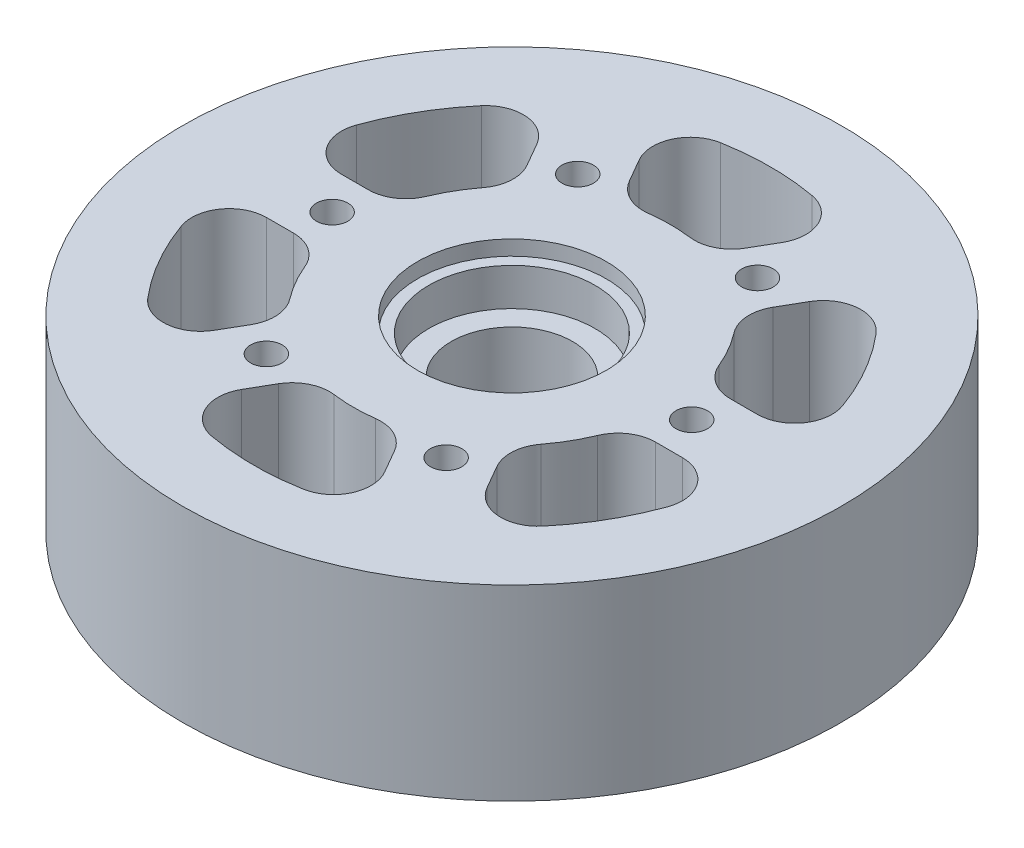
SolidWorks part; units mm, degrees
ref_plane "前视基准面" through (0, 0, 0) normal (0, 0, 1) x (1, 0, 0)
ref_plane "上视基准面" through (0, 0, 0) normal (0, 1, 0) x (1, 0, 0)
ref_plane "右视基准面" through (0, 0, 0) normal (1, 0, 0) x (0, 0, -1)
sketch "草图1" plane through (0, 0, 0) normal (0, 1, 0) x (1, 0, 0)
  circle A0 centre (0, 0) radius 52.5
  circle A1 centre (0, 0) radius 11.15
  dimension "D1" = 105
  dimension "D2" = 22.3
extrude "凸台-拉伸1" add sketch "草图1" along normal blind 25
sketch "草图2" plane through (0, 25, 0) normal (0, 1, 0) x (1, 0, 0)
  line L0 (-34.5, 0) -> (-21.15, 0)
  line L1 (-34.5, -5) -> (-21.15, -5)
  line L2 (-34.5, 5) -> (-21.15, 5)
  line L3 (-21.15, 5) -> (-20.5505, 5)
  line L4 (-21.15, -5) -> (-20.5505, -5)
  line L5 (-12.9199, 32.3779) -> (-6.2449, 20.8164)
  line L6 (-6.2449, 20.8164) -> (-5.9451, 20.2972)
  line L7 (-21.5801, 27.3779) -> (-14.9051, 15.8164)
  line L8 (-14.9051, 15.8164) -> (-14.6054, 15.2972)
  line L9 (21.5801, 27.3779) -> (14.9051, 15.8164)
  line L10 (14.9051, 15.8164) -> (14.6054, 15.2972)
  line L11 (12.9199, 32.3779) -> (6.2449, 20.8164)
  line L12 (6.2449, 20.8164) -> (5.9451, 20.2972)
  line L13 (34.5, -5) -> (21.15, -5)
  line L14 (21.15, -5) -> (20.5505, -5)
  line L15 (34.5, 5) -> (21.15, 5)
  line L16 (21.15, 5) -> (20.5505, 5)
  line L17 (12.9199, -32.3779) -> (6.2449, -20.8164)
  line L18 (6.2449, -20.8164) -> (5.9451, -20.2972)
  line L19 (21.5801, -27.3779) -> (14.9051, -15.8164)
  line L20 (14.9051, -15.8164) -> (14.6054, -15.2972)
  line L21 (-21.5801, -27.3779) -> (-14.9051, -15.8164)
  line L22 (-14.9051, -15.8164) -> (-14.6054, -15.2972)
  line L23 (-12.9199, -32.3779) -> (-6.2449, -20.8164)
  line L24 (-6.2449, -20.8164) -> (-5.9451, -20.2972)
  circle A0 centre (0, 0) radius 21.15
  circle A1 centre (0, 0) radius 34.5
  circle A2 centre (0, 0) radius 52.5 construction
  circle A3 centre (0, 0) radius 11.15 construction
  dimension "D1" = 18
  dimension "D2" = 10
  dimension "D3" = 5
  dimension "D5" = 6
  dimension "D4" = 5
extrude "切除-拉伸1" cut sketch "草图2" against normal blind 30 contours L7 A1 L2 L3 A0 L8
pattern_circular "阵列(圆周)1" count 6 over 360 about axis through (0, 25, 0) along (0, -1, 0) of "切除-拉伸1"
fillet "圆角1" radius 5 24 edges at (20.5505, 12.5, -5) (14.6054, 12.5, -15.2972) (21.398, 12.5, -27.0624) (34.1358, 12.5, -5) (-20.5505, 12.5, 5) (-14.6054, 12.5, 15.2972) (-21.398, 12.5, 27.0624) (-34.1358, 12.5, 5) (5.9451, 12.5, -20.2972) (-5.9451, 12.5, -20.2972) (-12.7378, 12.5, -32.0624) (12.7378, 12.5, -32.0624) (-14.6054, 12.5, -15.2972) (-20.5505, 12.5, -5) (-34.1358, 12.5, -5) (-5.9451, 12.5, 20.2972) (5.9451, 12.5, 20.2972) (12.7378, 12.5, 32.0624) (-12.7378, 12.5, 32.0624) (14.6054, 12.5, 15.2972) (20.5505, 12.5, 5) (34.1358, 12.5, 5) (21.398, 12.5, 27.0624) (-21.398, 12.5, -27.0624)
sketch "草图3" plane through (0, 25, 0) normal (0, 1, 0) x (1, 0, 0)
  circle A0 centre (0, 0) radius 44
  circle M2 centre (0, 0) radius 52.5
  dimension "D1" = 88
extrude "切除-拉伸2" cut sketch "草图3" against normal blind 30 contours A0 M2
sketch "草图5" plane through (0, 25, 0) normal (0, 1, 0) x (1, 0, 0)
  line L0 (0, 0) -> (24, 0)
  circle A0 centre (0, 0) radius 24
  circle A1 centre (24, 0) radius 2.1
  dimension "D1" = 48
  dimension "D2" = 4.2
extrude "切除-拉伸3" cut sketch "草图5" against normal blind 44 contours A1
pattern_circular "阵列(圆周)2" count 6 over 360 about axis through (0, 0, 0) along (0, 1, 0) of "切除-拉伸3"
sketch "草图6" plane through (0, 0, 0) normal (0, -1, 0) x (-1, 0, 0)
  arc A0 (12.5062, -0.2944) -> (12.5062, 0.2944) centre (0, 0) ccw
  arc A1 (12.237, 2.5976) -> (12.1012, 3.1706) centre (0, 0) ccw
  arc A2 (11.308, 5.3496) -> (11.0438, 5.8759) centre (0, 0) ccw
  arc A3 (9.7695, 7.8133) -> (9.391, 8.2643) centre (0, 0) ccw
  arc A4 (7.7043, 9.8557) -> (7.232, 10.2073) centre (0, 0) ccw
  arc A5 (5.2238, 11.3667) -> (4.6831, 11.6) centre (0, 0) ccw
  arc A6 (2.4616, 12.265) -> (1.8817, 12.3673) centre (0, 0) ccw
  arc A7 (-0.4332, 12.5021) -> (-1.0211, 12.4679) centre (0, 0) ccw
  arc A8 (-3.3048, 12.0652) -> (-3.8689, 11.8963) centre (0, 0) ccw
  arc A9 (-5.9981, 10.9779) -> (-6.5081, 10.6834) centre (0, 0) ccw
  arc A10 (-8.3681, 9.2987) -> (-8.7964, 8.8946) centre (0, 0) ccw
  arc A11 (-10.287, 7.1182) -> (-10.6105, 6.6263) centre (0, 0) ccw
  arc A12 (-11.6512, 4.554) -> (-11.8526, 4.0007) centre (0, 0) ccw
  arc A13 (-12.3874, 1.7443) -> (-12.4558, 1.1594) centre (0, 0) ccw
  arc A14 (-12.4558, -1.1594) -> (-12.3874, -1.7443) centre (0, 0) ccw
  arc A15 (-11.8526, -4.0007) -> (-11.6512, -4.554) centre (0, 0) ccw
  arc A16 (-10.6105, -6.6263) -> (-10.287, -7.1182) centre (0, 0) ccw
  arc A17 (-8.7964, -8.8946) -> (-8.3681, -9.2987) centre (0, 0) ccw
  arc A18 (-6.5081, -10.6834) -> (-5.9981, -10.9779) centre (0, 0) ccw
  arc A19 (-3.8689, -11.8963) -> (-3.3048, -12.0652) centre (0, 0) ccw
  arc A20 (-1.0211, -12.4679) -> (-0.4332, -12.5021) centre (0, 0) ccw
  arc A21 (1.8817, -12.3673) -> (2.4616, -12.265) centre (0, 0) ccw
  arc A22 (4.6831, -11.6) -> (5.2238, -11.3667) centre (0, 0) ccw
  arc A23 (7.232, -10.2073) -> (7.7043, -9.8557) centre (0, 0) ccw
  arc A24 (9.391, -8.2643) -> (9.7695, -7.8133) centre (0, 0) ccw
  arc A25 (11.0438, -5.8759) -> (11.308, -5.3496) centre (0, 0) ccw
  arc A26 (12.1012, -3.1706) -> (12.237, -2.5976) centre (0, 0) ccw
  spline S0 degree 3 number of poles 68 (12.237, -2.5976) -> (12.5062, -0.2944)
  spline S1 degree 3 number of poles 68 (12.5062, 0.2944) -> (12.237, 2.5976)
  spline S2 degree 3 number of poles 68 (12.1012, 3.1706) -> (11.308, 5.3496)
  spline S3 degree 3 number of poles 68 (11.0438, 5.8759) -> (9.7695, 7.8133)
  spline S4 degree 3 number of poles 68 (9.391, 8.2643) -> (7.7043, 9.8557)
  spline S5 degree 3 number of poles 68 (7.232, 10.2073) -> (5.2238, 11.3667)
  spline S6 degree 3 number of poles 68 (4.6831, 11.6) -> (2.4616, 12.265)
  spline S7 degree 3 number of poles 68 (1.8817, 12.3673) -> (-0.4332, 12.5021)
  spline S8 degree 3 number of poles 68 (-1.0211, 12.4679) -> (-3.3048, 12.0652)
  spline S9 degree 3 number of poles 68 (-3.8689, 11.8963) -> (-5.9981, 10.9779)
  spline S10 degree 3 number of poles 68 (-6.5081, 10.6834) -> (-8.3681, 9.2987)
  spline S11 degree 3 number of poles 68 (-8.7964, 8.8946) -> (-10.287, 7.1182)
  spline S12 degree 3 number of poles 68 (-10.6105, 6.6263) -> (-11.6512, 4.554)
  spline S13 degree 3 number of poles 68 (-11.8526, 4.0007) -> (-12.3874, 1.7443)
  spline S14 degree 3 number of poles 68 (-12.4558, 1.1594) -> (-12.4558, -1.1594)
  spline S15 degree 3 number of poles 68 (-12.3874, -1.7443) -> (-11.8526, -4.0007)
  spline S16 degree 3 number of poles 68 (-11.6512, -4.554) -> (-10.6105, -6.6263)
  spline S17 degree 3 number of poles 68 (-10.287, -7.1182) -> (-8.7964, -8.8946)
  spline S18 degree 3 number of poles 68 (-8.3681, -9.2987) -> (-6.5081, -10.6834)
  spline S19 degree 3 number of poles 68 (-5.9981, -10.9779) -> (-3.8689, -11.8963)
  spline S20 degree 3 number of poles 68 (-3.3048, -12.0652) -> (-1.0211, -12.4679)
  spline S21 degree 3 number of poles 68 (-0.4332, -12.5021) -> (1.8817, -12.3673)
  spline S22 degree 3 number of poles 68 (2.4616, -12.265) -> (4.6831, -11.6)
  spline S23 degree 3 number of poles 68 (5.2238, -11.3667) -> (7.232, -10.2073)
  spline S24 degree 3 number of poles 68 (7.7043, -9.8557) -> (9.391, -8.2643)
  spline S25 degree 3 number of poles 68 (9.7695, -7.8133) -> (11.0438, -5.8759)
  spline S26 degree 3 number of poles 68 (11.308, -5.3496) -> (12.1012, -3.1706)
  dimension "D1" = 0
extrude "凸台-拉伸2" add sketch "草图6" along normal blind 16.5
sketch "草图7" plane through (0, 0, 0) normal (0, -1, 0) x (1, 0, 0)
  circle A0 centre (0, 0) radius 31.75
  circle A2 centre (0, 0) radius 8.1
  dimension "D1" = 63.5
  dimension "D2" = 16.2
extrude "切除-拉伸4" cut sketch "草图7" along normal blind 74 contours A2
sketch "草图8" plane through (0, 25, 0) normal (0, 1, 0) x (1, 0, 0)
  circle A0 centre (0, 0) radius 8.1
  circle A1 centre (0, 0) radius 11.15
extrude "凸台-拉伸3" add sketch "草图8" against normal up to surface (25 mm away) up to face at (0, 0, -8.1)
sketch "草图9" plane through (0, 25, 0) normal (0, 1, 0) x (1, 0, 0)
  circle A0 centre (0, 0) radius 11.1
  dimension "D1" = 22.2
extrude "切除-拉伸5" cut sketch "草图9" against normal blind 7
sketch "草图10" plane through (0, 25, 0) normal (0, 1, 0) x (1, 0, 0)
  circle A0 centre (0, 0) radius 12.6
  dimension "D1" = 25.2
extrude "切除-拉伸6" cut sketch "草图10" against normal blind 2
sketch "草图11" plane through (0, -16.5, 0) normal (0, -1, 0) x (1, 0, 0)
  circle A0 centre (0, 0) radius 9.1
  dimension "D1" = 18.2
extrude "切除-拉伸7" cut sketch "草图11" against normal blind 1.1
sketch "草图12" plane through (0, 0, 0) normal (0, -1, 0) x (1, 0, 0)
  circle A0 centre (0, 0) radius 15.5096
  arc A1 (-11.0438, 5.8759) -> (-11.308, 5.3496) centre (0, 0) ccw construction
  arc A29 (-12.5062, 0.2944) -> (-12.5062, -0.2944) centre (0, 0) ccw
  arc A30 (-12.237, -2.5976) -> (-12.1012, -3.1706) centre (0, 0) ccw
  arc A31 (-11.308, -5.3496) -> (-11.0438, -5.8759) centre (0, 0) ccw
  arc A32 (-9.7695, -7.8133) -> (-9.391, -8.2643) centre (0, 0) ccw
  arc A33 (-7.7043, -9.8557) -> (-7.232, -10.2073) centre (0, 0) ccw
  arc A34 (-5.2238, -11.3667) -> (-4.6831, -11.6) centre (0, 0) ccw
  arc A35 (-2.4616, -12.265) -> (-1.8817, -12.3673) centre (0, 0) ccw
  arc A36 (0.4332, -12.5021) -> (1.0211, -12.4679) centre (0, 0) ccw
  arc A37 (3.3048, -12.0652) -> (3.8689, -11.8963) centre (0, 0) ccw
  arc A38 (5.9981, -10.9779) -> (6.5081, -10.6834) centre (0, 0) ccw
  arc A39 (8.3681, -9.2987) -> (8.7964, -8.8946) centre (0, 0) ccw
  arc A40 (10.287, -7.1182) -> (10.6105, -6.6263) centre (0, 0) ccw
  arc A41 (11.6512, -4.554) -> (11.8526, -4.0007) centre (0, 0) ccw
  arc A42 (12.3874, -1.7443) -> (12.4558, -1.1594) centre (0, 0) ccw
  arc A43 (12.4558, 1.1594) -> (12.3874, 1.7443) centre (0, 0) ccw
  arc A44 (11.8526, 4.0007) -> (11.6512, 4.554) centre (0, 0) ccw
  arc A45 (10.6105, 6.6263) -> (10.287, 7.1182) centre (0, 0) ccw
  arc A46 (8.7964, 8.8946) -> (8.3681, 9.2987) centre (0, 0) ccw
  arc A47 (6.5081, 10.6834) -> (5.9981, 10.9779) centre (0, 0) ccw
  arc A48 (3.8689, 11.8963) -> (3.3048, 12.0652) centre (0, 0) ccw
  arc A49 (1.0211, 12.4679) -> (0.4332, 12.5021) centre (0, 0) ccw
  arc A50 (-1.8817, 12.3673) -> (-2.4616, 12.265) centre (0, 0) ccw
  arc A51 (-4.6831, 11.6) -> (-5.2238, 11.3667) centre (0, 0) ccw
  arc A52 (-7.232, 10.2073) -> (-7.7043, 9.8557) centre (0, 0) ccw
  arc A53 (-9.391, 8.2643) -> (-9.7695, 7.8133) centre (0, 0) ccw
  arc A54 (-11.0438, 5.8759) -> (-11.308, 5.3496) centre (0, 0) ccw
  arc A55 (-12.1012, 3.1706) -> (-12.237, 2.5976) centre (0, 0) ccw
  arc A56 (-12.5062, 0.2944) -> (-12.5062, -0.2944) centre (0, 0) ccw
  arc A57 (-12.237, -2.5976) -> (-12.1012, -3.1706) centre (0, 0) ccw
  arc A58 (-11.308, -5.3496) -> (-11.0438, -5.8759) centre (0, 0) ccw
  arc A59 (-9.7695, -7.8133) -> (-9.391, -8.2643) centre (0, 0) ccw
  arc A60 (-7.7043, -9.8557) -> (-7.232, -10.2073) centre (0, 0) ccw
  arc A61 (-5.2238, -11.3667) -> (-4.6831, -11.6) centre (0, 0) ccw
  arc A62 (-2.4616, -12.265) -> (-1.8817, -12.3673) centre (0, 0) ccw
  arc A63 (0.4332, -12.5021) -> (1.0211, -12.4679) centre (0, 0) ccw
  arc A64 (3.3048, -12.0652) -> (3.8689, -11.8963) centre (0, 0) ccw
  arc A65 (5.9981, -10.9779) -> (6.5081, -10.6834) centre (0, 0) ccw
  arc A66 (8.3681, -9.2987) -> (8.7964, -8.8946) centre (0, 0) ccw
  arc A67 (10.287, -7.1182) -> (10.6105, -6.6263) centre (0, 0) ccw
  arc A68 (11.6512, -4.554) -> (11.8526, -4.0007) centre (0, 0) ccw
  arc A69 (12.3874, -1.7443) -> (12.4558, -1.1594) centre (0, 0) ccw
  arc A70 (12.4558, 1.1594) -> (12.3874, 1.7443) centre (0, 0) ccw
  arc A71 (11.8526, 4.0007) -> (11.6512, 4.554) centre (0, 0) ccw
  arc A72 (10.6105, 6.6263) -> (10.287, 7.1182) centre (0, 0) ccw
  arc A73 (8.7964, 8.8946) -> (8.3681, 9.2987) centre (0, 0) ccw
  arc A74 (6.5081, 10.6834) -> (5.9981, 10.9779) centre (0, 0) ccw
  arc A75 (3.8689, 11.8963) -> (3.3048, 12.0652) centre (0, 0) ccw
  arc A76 (1.0211, 12.4679) -> (0.4332, 12.5021) centre (0, 0) ccw
  arc A77 (-1.8817, 12.3673) -> (-2.4616, 12.265) centre (0, 0) ccw
  arc A78 (-4.6831, 11.6) -> (-5.2238, 11.3667) centre (0, 0) ccw
  arc A79 (-7.232, 10.2073) -> (-7.7043, 9.8557) centre (0, 0) ccw
  arc A80 (-9.391, 8.2643) -> (-9.7695, 7.8133) centre (0, 0) ccw
  arc A81 (-11.0438, 5.8759) -> (-11.308, 5.3496) centre (0, 0) ccw
  arc A82 (-12.1012, 3.1706) -> (-12.237, 2.5976) centre (0, 0) ccw
  spline S27 degree 3 number of poles 68 (-12.237, 2.5976) -> (-12.5062, 0.2944)
  spline S28 degree 3 number of poles 68 (-12.5062, -0.2944) -> (-12.237, -2.5976)
  spline S29 degree 3 number of poles 68 (-12.1012, -3.1706) -> (-11.308, -5.3496)
  spline S30 degree 3 number of poles 68 (-11.0438, -5.8759) -> (-9.7695, -7.8133)
  spline S31 degree 3 number of poles 68 (-9.391, -8.2643) -> (-7.7043, -9.8557)
  spline S32 degree 3 number of poles 68 (-7.232, -10.2073) -> (-5.2238, -11.3667)
  spline S33 degree 3 number of poles 68 (-4.6831, -11.6) -> (-2.4616, -12.265)
  spline S34 degree 3 number of poles 68 (-1.8817, -12.3673) -> (0.4332, -12.5021)
  spline S35 degree 3 number of poles 68 (1.0211, -12.4679) -> (3.3048, -12.0652)
  spline S36 degree 3 number of poles 68 (3.8689, -11.8963) -> (5.9981, -10.9779)
  spline S37 degree 3 number of poles 68 (6.5081, -10.6834) -> (8.3681, -9.2987)
  spline S38 degree 3 number of poles 68 (8.7964, -8.8946) -> (10.287, -7.1182)
  spline S39 degree 3 number of poles 68 (10.6105, -6.6263) -> (11.6512, -4.554)
  spline S40 degree 3 number of poles 68 (11.8526, -4.0007) -> (12.3874, -1.7443)
  spline S41 degree 3 number of poles 68 (12.4558, -1.1594) -> (12.4558, 1.1594)
  spline S42 degree 3 number of poles 68 (12.3874, 1.7443) -> (11.8526, 4.0007)
  spline S43 degree 3 number of poles 68 (11.6512, 4.554) -> (10.6105, 6.6263)
  spline S44 degree 3 number of poles 68 (10.287, 7.1182) -> (8.7964, 8.8946)
  spline S45 degree 3 number of poles 68 (8.3681, 9.2987) -> (6.5081, 10.6834)
  spline S46 degree 3 number of poles 68 (5.9981, 10.9779) -> (3.8689, 11.8963)
  spline S47 degree 3 number of poles 68 (3.3048, 12.0652) -> (1.0211, 12.4679)
  spline S48 degree 3 number of poles 68 (0.4332, 12.5021) -> (-1.8817, 12.3673)
  spline S49 degree 3 number of poles 68 (-2.4616, 12.265) -> (-4.6831, 11.6)
  spline S50 degree 3 number of poles 68 (-5.2238, 11.3667) -> (-7.232, 10.2073)
  spline S51 degree 3 number of poles 68 (-7.7043, 9.8557) -> (-9.391, 8.2643)
  spline S52 degree 3 number of poles 68 (-9.7695, 7.8133) -> (-11.0438, 5.8759)
  spline S53 degree 3 number of poles 68 (-11.308, 5.3496) -> (-12.1012, 3.1706)
  spline S54 degree 3 number of poles 68 (-12.237, 2.5976) -> (-12.5062, 0.2944)
  spline S55 degree 3 number of poles 68 (-12.5062, -0.2944) -> (-12.237, -2.5976)
  spline S56 degree 3 number of poles 68 (-12.1012, -3.1706) -> (-11.308, -5.3496)
  spline S57 degree 3 number of poles 68 (-11.0438, -5.8759) -> (-9.7695, -7.8133)
  spline S58 degree 3 number of poles 68 (-9.391, -8.2643) -> (-7.7043, -9.8557)
  spline S59 degree 3 number of poles 68 (-7.232, -10.2073) -> (-5.2238, -11.3667)
  spline S60 degree 3 number of poles 68 (-4.6831, -11.6) -> (-2.4616, -12.265)
  spline S61 degree 3 number of poles 68 (-1.8817, -12.3673) -> (0.4332, -12.5021)
  spline S62 degree 3 number of poles 68 (1.0211, -12.4679) -> (3.3048, -12.0652)
  spline S63 degree 3 number of poles 68 (3.8689, -11.8963) -> (5.9981, -10.9779)
  spline S64 degree 3 number of poles 68 (6.5081, -10.6834) -> (8.3681, -9.2987)
  spline S65 degree 3 number of poles 68 (8.7964, -8.8946) -> (10.287, -7.1182)
  spline S66 degree 3 number of poles 68 (10.6105, -6.6263) -> (11.6512, -4.554)
  spline S67 degree 3 number of poles 68 (11.8526, -4.0007) -> (12.3874, -1.7443)
  spline S68 degree 3 number of poles 68 (12.4558, -1.1594) -> (12.4558, 1.1594)
  spline S69 degree 3 number of poles 68 (12.3874, 1.7443) -> (11.8526, 4.0007)
  spline S70 degree 3 number of poles 68 (11.6512, 4.554) -> (10.6105, 6.6263)
  spline S71 degree 3 number of poles 68 (10.287, 7.1182) -> (8.7964, 8.8946)
  spline S72 degree 3 number of poles 68 (8.3681, 9.2987) -> (6.5081, 10.6834)
  spline S73 degree 3 number of poles 68 (5.9981, 10.9779) -> (3.8689, 11.8963)
  spline S74 degree 3 number of poles 68 (3.3048, 12.0652) -> (1.0211, 12.4679)
  spline S75 degree 3 number of poles 68 (0.4332, 12.5021) -> (-1.8817, 12.3673)
  spline S76 degree 3 number of poles 68 (-2.4616, 12.265) -> (-4.6831, 11.6)
  spline S77 degree 3 number of poles 68 (-5.2238, 11.3667) -> (-7.232, 10.2073)
  spline S78 degree 3 number of poles 68 (-7.7043, 9.8557) -> (-9.391, 8.2643)
  spline S79 degree 3 number of poles 68 (-9.7695, 7.8133) -> (-11.0438, 5.8759)
  spline S80 degree 3 number of poles 68 (-11.308, 5.3496) -> (-12.1012, 3.1706)
  dimension "D1" = 3
  dimension "D2" = 0
extrude "凸台-拉伸4" add sketch "草图12" along normal blind 8.5
chamfer "倒角1" distance 1 angle 45 1 edges at (0, -8.5, -15.5096)
sketch "草图13" plane through (0, 0, 0) normal (0, -1, 0) x (1, 0, 0)
  circle A0 centre (0, 0) radius 15.5096
extrude "切除-拉伸8" cut sketch "草图13" along normal blind 33
sketch "草图14" plane through (0, 0, 0) normal (0, -1, 0) x (1, 0, 0)
  circle A0 centre (0, 0) radius 9.1
  dimension "D1" = 18.2
extrude "切除-拉伸9" cut sketch "草图14" against normal blind 1.1
sketch "草图15" plane through (0, 0, 0) normal (0, -1, 0) x (1, 0, 0)
  line L2 (-18.2068, -21.5351) -> (-16.4113, -18.4253)
  line L3 (-24.1624, -5) -> (-27.7534, -5)
  line L4 (-18.2068, -21.5351) -> (-16.4113, -18.4253)
  line L5 (-24.1624, -5) -> (-27.7534, -5)
  line L6 (9.5466, -26.5351) -> (7.7511, -23.4253)
  line L7 (-7.7511, -23.4253) -> (-9.5466, -26.5351)
  line L8 (9.5466, -26.5351) -> (7.7511, -23.4253)
  line L9 (-7.7511, -23.4253) -> (-9.5466, -26.5351)
  line L10 (27.7534, -5) -> (24.1624, -5)
  line L11 (16.4113, -18.4253) -> (18.2068, -21.5351)
  line L12 (27.7534, -5) -> (24.1624, -5)
  line L13 (16.4113, -18.4253) -> (18.2068, -21.5351)
  line L14 (18.2068, 21.5351) -> (16.4113, 18.4253)
  line L15 (24.1624, 5) -> (27.7534, 5)
  line L16 (18.2068, 21.5351) -> (16.4113, 18.4253)
  line L17 (24.1624, 5) -> (27.7534, 5)
  line L18 (-9.5466, 26.5351) -> (-7.7511, 23.4253)
  line L19 (7.7511, 23.4253) -> (9.5466, 26.5351)
  line L20 (-9.5466, 26.5351) -> (-7.7511, 23.4253)
  line L21 (7.7511, 23.4253) -> (9.5466, 26.5351)
  line L22 (-27.7534, 5) -> (-24.1624, 5)
  line L23 (-16.4113, 18.4253) -> (-18.2068, 21.5351)
  line L24 (-27.7534, 5) -> (-24.1624, 5)
  line L25 (-16.4113, 18.4253) -> (-18.2068, 21.5351)
  circle A1 centre (0, 0) radius 44
  circle A2 centre (0, 0) radius 44
  circle A3 centre (24, 0) radius 2.1
  circle A4 centre (24, 0) radius 2.1
  circle A5 centre (12, 20.7846) radius 2.1
  circle A6 centre (12, 20.7846) radius 2.1
  circle A7 centre (-12, 20.7846) radius 2.1
  arc A8 (-26.3568, -22.2614) -> (-18.2068, -21.5351) centre (-22.5369, -19.0351) ccw
  arc A9 (-32.4573, -11.6949) -> (-26.3568, -22.2614) centre (0, 0) ccw
  arc A10 (-27.7534, -5) -> (-32.4573, -11.6949) centre (-27.7534, -10) ccw
  arc A11 (-19.5425, -8.088) -> (-24.1624, -5) centre (-24.1624, -10) ccw
  arc A12 (-19.5425, -8.088) -> (-16.7756, -12.8803) centre (0, 0) ccw
  arc A13 (-16.4113, -18.4253) -> (-16.7756, -12.8803) centre (-20.7415, -15.9253) ccw
  arc A14 (-26.3568, -22.2614) -> (-18.2068, -21.5351) centre (-22.5369, -19.0351) ccw
  arc A15 (-32.4573, -11.6949) -> (-26.3568, -22.2614) centre (0, 0) ccw
  arc A16 (-27.7534, -5) -> (-32.4573, -11.6949) centre (-27.7534, -10) ccw
  arc A17 (-19.5425, -8.088) -> (-24.1624, -5) centre (-24.1624, -10) ccw
  arc A18 (-19.5425, -8.088) -> (-16.7756, -12.8803) centre (0, 0) ccw
  arc A19 (-16.4113, -18.4253) -> (-16.7756, -12.8803) centre (-20.7415, -15.9253) ccw
  arc A20 (6.1006, -33.9563) -> (9.5466, -26.5351) centre (5.2164, -29.0351) ccw
  arc A21 (-6.1006, -33.9563) -> (6.1006, -33.9563) centre (0, 0) ccw
  arc A22 (-9.5466, -26.5351) -> (-6.1006, -33.9563) centre (-5.2164, -29.0351) ccw
  arc A23 (-2.7669, -20.9682) -> (-7.7511, -23.4253) centre (-3.421, -25.9253) ccw
  arc A24 (-2.7669, -20.9682) -> (2.7669, -20.9682) centre (0, 0) ccw
  arc A25 (7.7511, -23.4253) -> (2.7669, -20.9682) centre (3.421, -25.9253) ccw
  arc A26 (6.1006, -33.9563) -> (9.5466, -26.5351) centre (5.2164, -29.0351) ccw
  arc A27 (-6.1006, -33.9563) -> (6.1006, -33.9563) centre (0, 0) ccw
  arc A28 (-9.5466, -26.5351) -> (-6.1006, -33.9563) centre (-5.2164, -29.0351) ccw
  arc A29 (-2.7669, -20.9682) -> (-7.7511, -23.4253) centre (-3.421, -25.9253) ccw
  arc A30 (-2.7669, -20.9682) -> (2.7669, -20.9682) centre (0, 0) ccw
  arc A31 (7.7511, -23.4253) -> (2.7669, -20.9682) centre (3.421, -25.9253) ccw
  arc A32 (32.4573, -11.6949) -> (27.7534, -5) centre (27.7534, -10) ccw
  arc A33 (26.3568, -22.2614) -> (32.4573, -11.6949) centre (0, 0) ccw
  arc A34 (18.2068, -21.5351) -> (26.3568, -22.2614) centre (22.5369, -19.0351) ccw
  arc A35 (16.7756, -12.8803) -> (16.4113, -18.4253) centre (20.7415, -15.9253) ccw
  arc A36 (16.7756, -12.8803) -> (19.5425, -8.088) centre (0, 0) ccw
  arc A37 (24.1624, -5) -> (19.5425, -8.088) centre (24.1624, -10) ccw
  arc A38 (32.4573, -11.6949) -> (27.7534, -5) centre (27.7534, -10) ccw
  arc A39 (26.3568, -22.2614) -> (32.4573, -11.6949) centre (0, 0) ccw
  arc A40 (18.2068, -21.5351) -> (26.3568, -22.2614) centre (22.5369, -19.0351) ccw
  arc A41 (16.7756, -12.8803) -> (16.4113, -18.4253) centre (20.7415, -15.9253) ccw
  arc A42 (16.7756, -12.8803) -> (19.5425, -8.088) centre (0, 0) ccw
  arc A43 (24.1624, -5) -> (19.5425, -8.088) centre (24.1624, -10) ccw
  arc A44 (26.3568, 22.2614) -> (18.2068, 21.5351) centre (22.5369, 19.0351) ccw
  arc A45 (32.4573, 11.6949) -> (26.3568, 22.2614) centre (0, 0) ccw
  arc A46 (27.7534, 5) -> (32.4573, 11.6949) centre (27.7534, 10) ccw
  arc A47 (19.5425, 8.088) -> (24.1624, 5) centre (24.1624, 10) ccw
  arc A48 (19.5425, 8.088) -> (16.7756, 12.8803) centre (0, 0) ccw
  arc A49 (16.4113, 18.4253) -> (16.7756, 12.8803) centre (20.7415, 15.9253) ccw
  arc A50 (26.3568, 22.2614) -> (18.2068, 21.5351) centre (22.5369, 19.0351) ccw
  arc A51 (32.4573, 11.6949) -> (26.3568, 22.2614) centre (0, 0) ccw
  arc A52 (27.7534, 5) -> (32.4573, 11.6949) centre (27.7534, 10) ccw
  arc A53 (19.5425, 8.088) -> (24.1624, 5) centre (24.1624, 10) ccw
  arc A54 (19.5425, 8.088) -> (16.7756, 12.8803) centre (0, 0) ccw
  arc A55 (16.4113, 18.4253) -> (16.7756, 12.8803) centre (20.7415, 15.9253) ccw
  arc A56 (-6.1006, 33.9563) -> (-9.5466, 26.5351) centre (-5.2164, 29.0351) ccw
  arc A57 (6.1006, 33.9563) -> (-6.1006, 33.9563) centre (0, 0) ccw
  arc A58 (9.5466, 26.5351) -> (6.1006, 33.9563) centre (5.2164, 29.0351) ccw
  arc A59 (2.7669, 20.9682) -> (7.7511, 23.4253) centre (3.421, 25.9253) ccw
  arc A60 (2.7669, 20.9682) -> (-2.7669, 20.9682) centre (0, 0) ccw
  arc A61 (-7.7511, 23.4253) -> (-2.7669, 20.9682) centre (-3.421, 25.9253) ccw
  arc A62 (-6.1006, 33.9563) -> (-9.5466, 26.5351) centre (-5.2164, 29.0351) ccw
  arc A63 (6.1006, 33.9563) -> (-6.1006, 33.9563) centre (0, 0) ccw
  arc A64 (9.5466, 26.5351) -> (6.1006, 33.9563) centre (5.2164, 29.0351) ccw
  arc A65 (2.7669, 20.9682) -> (7.7511, 23.4253) centre (3.421, 25.9253) ccw
  arc A66 (2.7669, 20.9682) -> (-2.7669, 20.9682) centre (0, 0) ccw
  arc A67 (-7.7511, 23.4253) -> (-2.7669, 20.9682) centre (-3.421, 25.9253) ccw
  arc A68 (-32.4573, 11.6949) -> (-27.7534, 5) centre (-27.7534, 10) ccw
  arc A69 (-26.3568, 22.2614) -> (-32.4573, 11.6949) centre (0, 0) ccw
  arc A70 (-18.2068, 21.5351) -> (-26.3568, 22.2614) centre (-22.5369, 19.0351) ccw
  arc A71 (-16.7756, 12.8803) -> (-16.4113, 18.4253) centre (-20.7415, 15.9253) ccw
  arc A72 (-16.7756, 12.8803) -> (-19.5425, 8.088) centre (0, 0) ccw
  arc A73 (-24.1624, 5) -> (-19.5425, 8.088) centre (-24.1624, 10) ccw
  arc A74 (-32.4573, 11.6949) -> (-27.7534, 5) centre (-27.7534, 10) ccw
  arc A75 (-26.3568, 22.2614) -> (-32.4573, 11.6949) centre (0, 0) ccw
  arc A76 (-18.2068, 21.5351) -> (-26.3568, 22.2614) centre (-22.5369, 19.0351) ccw
  arc A77 (-16.7756, 12.8803) -> (-16.4113, 18.4253) centre (-20.7415, 15.9253) ccw
  arc A78 (-16.7756, 12.8803) -> (-19.5425, 8.088) centre (0, 0) ccw
  arc A79 (-24.1624, 5) -> (-19.5425, 8.088) centre (-24.1624, 10) ccw
  circle A80 centre (-12, 20.7846) radius 2.1
  circle A81 centre (-24, 0) radius 2.1
  circle A82 centre (-24, 0) radius 2.1
  circle A83 centre (-12, -20.7846) radius 2.1
  circle A84 centre (-12, -20.7846) radius 2.1
  circle A85 centre (12, -20.7846) radius 2.1
  circle A86 centre (12, -20.7846) radius 2.1
  circle A87 centre (0, 0) radius 9.1
  circle A88 centre (0, 0) radius 9.1
  dimension "D1" = 0
  dimension "D2" = 0
  dimension "D3" = 0
  dimension "D4" = 0
  dimension "D5" = 0
  dimension "D6" = 0
  dimension "D7" = 0
  dimension "D8" = 0
  dimension "D9" = 0
  dimension "D10" = 0
  dimension "D11" = 0
  dimension "D12" = 0
  dimension "D13" = 0
  dimension "D14" = 0
sketch "草图16" plane through (0, 0, 0) normal (0, -1, 0) x (1, 0, 0)
  line L2 (27.7534, -5) -> (24.1624, -5)
  line L3 (16.4113, -18.4253) -> (18.2068, -21.5351)
  line L4 (27.7534, -5) -> (24.1624, -5)
  line L5 (16.4113, -18.4253) -> (18.2068, -21.5351)
  line L6 (18.2068, 21.5351) -> (16.4113, 18.4253)
  line L7 (24.1624, 5) -> (27.7534, 5)
  line L8 (18.2068, 21.5351) -> (16.4113, 18.4253)
  line L9 (24.1624, 5) -> (27.7534, 5)
  line L10 (-9.5466, 26.5351) -> (-7.7511, 23.4253)
  line L11 (7.7511, 23.4253) -> (9.5466, 26.5351)
  line L12 (-9.5466, 26.5351) -> (-7.7511, 23.4253)
  line L13 (7.7511, 23.4253) -> (9.5466, 26.5351)
  line L14 (-27.7534, 5) -> (-24.1624, 5)
  line L15 (-16.4113, 18.4253) -> (-18.2068, 21.5351)
  line L16 (-27.7534, 5) -> (-24.1624, 5)
  line L17 (-16.4113, 18.4253) -> (-18.2068, 21.5351)
  line L18 (-18.2068, -21.5351) -> (-16.4113, -18.4253)
  line L19 (-24.1624, -5) -> (-27.7534, -5)
  line L20 (-18.2068, -21.5351) -> (-16.4113, -18.4253)
  line L21 (-24.1624, -5) -> (-27.7534, -5)
  line L22 (9.5466, -26.5351) -> (7.7511, -23.4253)
  line L23 (-7.7511, -23.4253) -> (-9.5466, -26.5351)
  line L24 (9.5466, -26.5351) -> (7.7511, -23.4253)
  line L25 (-7.7511, -23.4253) -> (-9.5466, -26.5351)
  circle A1 centre (0, 0) radius 44
  circle A2 centre (0, 0) radius 44
  circle A3 centre (24, 0) radius 2.1
  circle A4 centre (24, 0) radius 2.1
  circle A5 centre (12, 20.7846) radius 2.1
  circle A6 centre (12, 20.7846) radius 2.1
  circle A7 centre (-12, 20.7846) radius 2.1
  arc A8 (32.4573, -11.6949) -> (27.7534, -5) centre (27.7534, -10) ccw
  arc A9 (26.3568, -22.2614) -> (32.4573, -11.6949) centre (0, 0) ccw
  arc A10 (18.2068, -21.5351) -> (26.3568, -22.2614) centre (22.5369, -19.0351) ccw
  arc A11 (16.7756, -12.8803) -> (16.4113, -18.4253) centre (20.7415, -15.9253) ccw
  arc A12 (16.7756, -12.8803) -> (19.5425, -8.088) centre (0, 0) ccw
  arc A13 (24.1624, -5) -> (19.5425, -8.088) centre (24.1624, -10) ccw
  arc A14 (32.4573, -11.6949) -> (27.7534, -5) centre (27.7534, -10) ccw
  arc A15 (26.3568, -22.2614) -> (32.4573, -11.6949) centre (0, 0) ccw
  arc A16 (18.2068, -21.5351) -> (26.3568, -22.2614) centre (22.5369, -19.0351) ccw
  arc A17 (16.7756, -12.8803) -> (16.4113, -18.4253) centre (20.7415, -15.9253) ccw
  arc A18 (16.7756, -12.8803) -> (19.5425, -8.088) centre (0, 0) ccw
  arc A19 (24.1624, -5) -> (19.5425, -8.088) centre (24.1624, -10) ccw
  arc A20 (26.3568, 22.2614) -> (18.2068, 21.5351) centre (22.5369, 19.0351) ccw
  arc A21 (32.4573, 11.6949) -> (26.3568, 22.2614) centre (0, 0) ccw
  arc A22 (27.7534, 5) -> (32.4573, 11.6949) centre (27.7534, 10) ccw
  arc A23 (19.5425, 8.088) -> (24.1624, 5) centre (24.1624, 10) ccw
  arc A24 (19.5425, 8.088) -> (16.7756, 12.8803) centre (0, 0) ccw
  arc A25 (16.4113, 18.4253) -> (16.7756, 12.8803) centre (20.7415, 15.9253) ccw
  arc A26 (26.3568, 22.2614) -> (18.2068, 21.5351) centre (22.5369, 19.0351) ccw
  arc A27 (32.4573, 11.6949) -> (26.3568, 22.2614) centre (0, 0) ccw
  arc A28 (27.7534, 5) -> (32.4573, 11.6949) centre (27.7534, 10) ccw
  arc A29 (19.5425, 8.088) -> (24.1624, 5) centre (24.1624, 10) ccw
  arc A30 (19.5425, 8.088) -> (16.7756, 12.8803) centre (0, 0) ccw
  arc A31 (16.4113, 18.4253) -> (16.7756, 12.8803) centre (20.7415, 15.9253) ccw
  arc A32 (-6.1006, 33.9563) -> (-9.5466, 26.5351) centre (-5.2164, 29.0351) ccw
  arc A33 (6.1006, 33.9563) -> (-6.1006, 33.9563) centre (0, 0) ccw
  arc A34 (9.5466, 26.5351) -> (6.1006, 33.9563) centre (5.2164, 29.0351) ccw
  arc A35 (2.7669, 20.9682) -> (7.7511, 23.4253) centre (3.421, 25.9253) ccw
  arc A36 (2.7669, 20.9682) -> (-2.7669, 20.9682) centre (0, 0) ccw
  arc A37 (-7.7511, 23.4253) -> (-2.7669, 20.9682) centre (-3.421, 25.9253) ccw
  arc A38 (-6.1006, 33.9563) -> (-9.5466, 26.5351) centre (-5.2164, 29.0351) ccw
  arc A39 (6.1006, 33.9563) -> (-6.1006, 33.9563) centre (0, 0) ccw
  arc A40 (9.5466, 26.5351) -> (6.1006, 33.9563) centre (5.2164, 29.0351) ccw
  arc A41 (2.7669, 20.9682) -> (7.7511, 23.4253) centre (3.421, 25.9253) ccw
  arc A42 (2.7669, 20.9682) -> (-2.7669, 20.9682) centre (0, 0) ccw
  arc A43 (-7.7511, 23.4253) -> (-2.7669, 20.9682) centre (-3.421, 25.9253) ccw
  arc A44 (-32.4573, 11.6949) -> (-27.7534, 5) centre (-27.7534, 10) ccw
  arc A45 (-26.3568, 22.2614) -> (-32.4573, 11.6949) centre (0, 0) ccw
  arc A46 (-18.2068, 21.5351) -> (-26.3568, 22.2614) centre (-22.5369, 19.0351) ccw
  arc A47 (-16.7756, 12.8803) -> (-16.4113, 18.4253) centre (-20.7415, 15.9253) ccw
  arc A48 (-16.7756, 12.8803) -> (-19.5425, 8.088) centre (0, 0) ccw
  arc A49 (-24.1624, 5) -> (-19.5425, 8.088) centre (-24.1624, 10) ccw
  arc A50 (-32.4573, 11.6949) -> (-27.7534, 5) centre (-27.7534, 10) ccw
  arc A51 (-26.3568, 22.2614) -> (-32.4573, 11.6949) centre (0, 0) ccw
  arc A52 (-18.2068, 21.5351) -> (-26.3568, 22.2614) centre (-22.5369, 19.0351) ccw
  arc A53 (-16.7756, 12.8803) -> (-16.4113, 18.4253) centre (-20.7415, 15.9253) ccw
  arc A54 (-16.7756, 12.8803) -> (-19.5425, 8.088) centre (0, 0) ccw
  arc A55 (-24.1624, 5) -> (-19.5425, 8.088) centre (-24.1624, 10) ccw
  circle A56 centre (-12, 20.7846) radius 2.1
  circle A57 centre (-24, 0) radius 2.1
  circle A58 centre (-24, 0) radius 2.1
  circle A59 centre (-12, -20.7846) radius 2.1
  circle A60 centre (-12, -20.7846) radius 2.1
  circle A61 centre (12, -20.7846) radius 2.1
  circle A62 centre (12, -20.7846) radius 2.1
  circle A63 centre (0, 0) radius 9.1
  circle A64 centre (0, 0) radius 9.1
  arc A70 (-26.3568, -22.2614) -> (-18.2068, -21.5351) centre (-22.5369, -19.0351) ccw
  arc A71 (-32.4573, -11.6949) -> (-26.3568, -22.2614) centre (0, 0) ccw
  arc A72 (-27.7534, -5) -> (-32.4573, -11.6949) centre (-27.7534, -10) ccw
  arc A73 (-19.5425, -8.088) -> (-24.1624, -5) centre (-24.1624, -10) ccw
  arc A74 (-19.5425, -8.088) -> (-16.7756, -12.8803) centre (0, 0) ccw
  arc A75 (-16.4113, -18.4253) -> (-16.7756, -12.8803) centre (-20.7415, -15.9253) ccw
  arc A76 (-26.3568, -22.2614) -> (-18.2068, -21.5351) centre (-22.5369, -19.0351) ccw
  arc A77 (-32.4573, -11.6949) -> (-26.3568, -22.2614) centre (0, 0) ccw
  arc A78 (-27.7534, -5) -> (-32.4573, -11.6949) centre (-27.7534, -10) ccw
  arc A79 (-19.5425, -8.088) -> (-24.1624, -5) centre (-24.1624, -10) ccw
  arc A80 (-19.5425, -8.088) -> (-16.7756, -12.8803) centre (0, 0) ccw
  arc A81 (-16.4113, -18.4253) -> (-16.7756, -12.8803) centre (-20.7415, -15.9253) ccw
  arc A82 (6.1006, -33.9563) -> (9.5466, -26.5351) centre (5.2164, -29.0351) ccw
  arc A83 (-6.1006, -33.9563) -> (6.1006, -33.9563) centre (0, 0) ccw
  arc A84 (-9.5466, -26.5351) -> (-6.1006, -33.9563) centre (-5.2164, -29.0351) ccw
  arc A85 (-2.7669, -20.9682) -> (-7.7511, -23.4253) centre (-3.421, -25.9253) ccw
  arc A86 (-2.7669, -20.9682) -> (2.7669, -20.9682) centre (0, 0) ccw
  arc A87 (7.7511, -23.4253) -> (2.7669, -20.9682) centre (3.421, -25.9253) ccw
  arc A88 (6.1006, -33.9563) -> (9.5466, -26.5351) centre (5.2164, -29.0351) ccw
  arc A89 (-6.1006, -33.9563) -> (6.1006, -33.9563) centre (0, 0) ccw
  arc A90 (-9.5466, -26.5351) -> (-6.1006, -33.9563) centre (-5.2164, -29.0351) ccw
  arc A91 (-2.7669, -20.9682) -> (-7.7511, -23.4253) centre (-3.421, -25.9253) ccw
  arc A92 (-2.7669, -20.9682) -> (2.7669, -20.9682) centre (0, 0) ccw
  arc A93 (7.7511, -23.4253) -> (2.7669, -20.9682) centre (3.421, -25.9253) ccw
  dimension "D1" = 0
  dimension "D2" = 0
  dimension "D3" = 0
  dimension "D4" = 0
  dimension "D5" = 0
  dimension "D6" = 0
  dimension "D7" = 0
  dimension "D8" = 0
  dimension "D9" = 0
  dimension "D10" = 0
  dimension "D11" = 0
  dimension "D12" = 0
  dimension "D13" = 0
  dimension "D14" = 0
